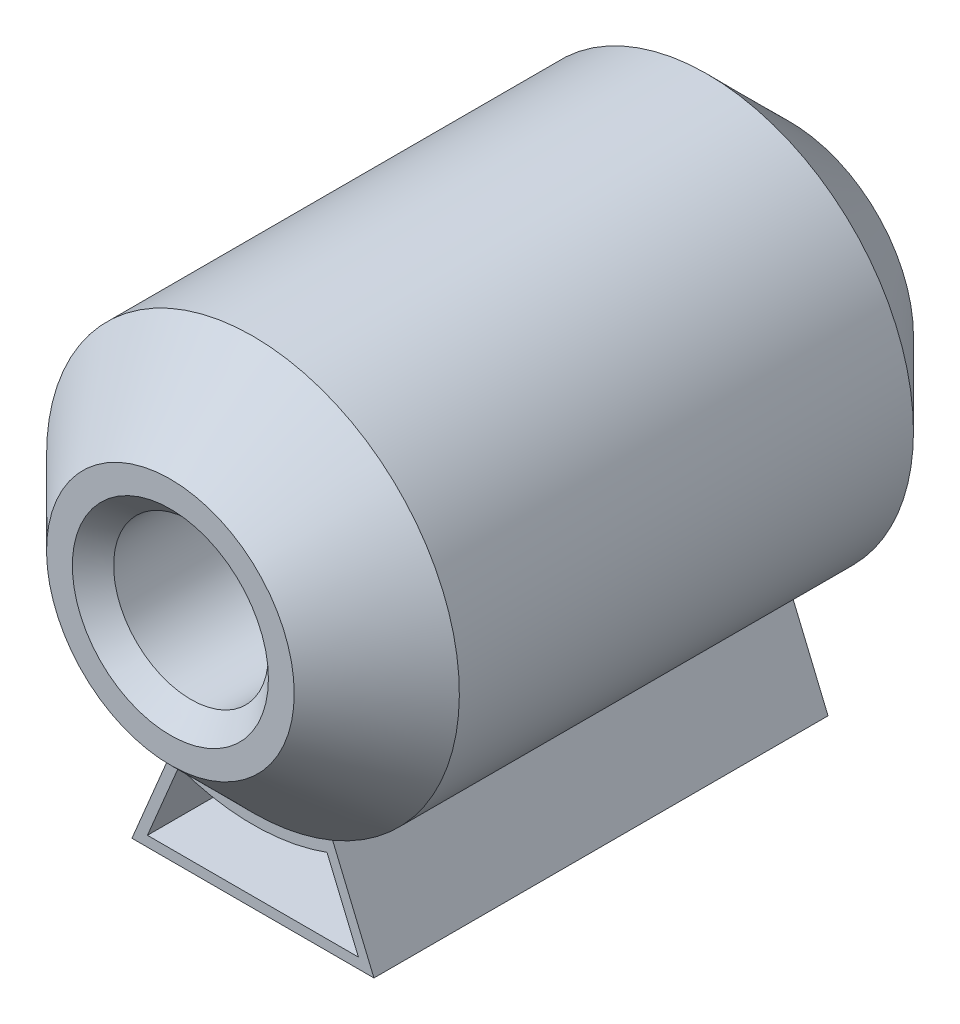
SolidWorks part; units mm, degrees
ref_plane "Front Plane" through (0, 0, 0) normal (0, 0, 1) x (1, 0, 0)
ref_plane "Top Plane" through (0, 0, 0) normal (0, 1, 0) x (1, 0, 0)
ref_plane "Right Plane" through (0, 0, 0) normal (1, 0, 0) x (0, 0, -1)
sketch "Sketch1" plane through (0, 0, 0) normal (0, 0, 1) x (1, 0, 0)
  circle A0 centre (0, 0) radius 10
  dimension "D1" = 20
extrude "Boss-Extrude1" add sketch "Sketch1" along normal mid plane 30
chamfer "Chamfer1" distance 4 angle 45 2 edges at (10, 0, -15) (10, 0, 15)
sketch "Sketch2" plane through (0, 0, 15) normal (0, 0, 1) x (1, 0, 0)
  circle A0 centre (0, 0) radius 3.75
  dimension "D1" = 7.5
extrude "Cut-Extrude1" cut sketch "Sketch2" against normal through all
chamfer "Chamfer2" distance 1 angle 45 2 edges at (3.75, 0, -15) (3.75, 0, 15)
ref_plane "Plane1" through (0, 0, 11) normal (0, 0, 1) x (1, 0, 0)
sketch "Sketch3" plane through (0, 0, 11) normal (0, 0, 1) x (1, 0, 0)
  line L0 (-3.8625, -9.2239) -> (-5.8625, -14)
  line L1 (-5.8625, -14) -> (5.8625, -14)
  line L2 (5.8625, -14) -> (3.8625, -9.2239)
  line L3 (-3.5899, -9.8673) -> (-5.1111, -13.5)
  line L4 (-5.1111, -13.5) -> (5.1111, -13.5)
  line L5 (5.1111, -13.5) -> (3.5899, -9.8673)
  circle A0 centre (0, 0) radius 10 construction
  arc A1 (3.8625, -9.2239) -> (-3.8625, -9.2239) centre (0, 0) cw
  arc A2 (3.5899, -9.8673) -> (-3.5899, -9.8673) centre (0, 0) cw
  point P7 (-4.0798, -9.2239)
  point P8 (0, 0)
  point P9 (7.5052, -14)
  point P10 (4.7653, -8.7916)
  point P11 (0, 0)
  dimension "D3" = 0.5
  dimension "D1" = 2
  dimension "D2" = 4
extrude "Boss-Extrude2" add sketch "Sketch3" against normal blind 22
